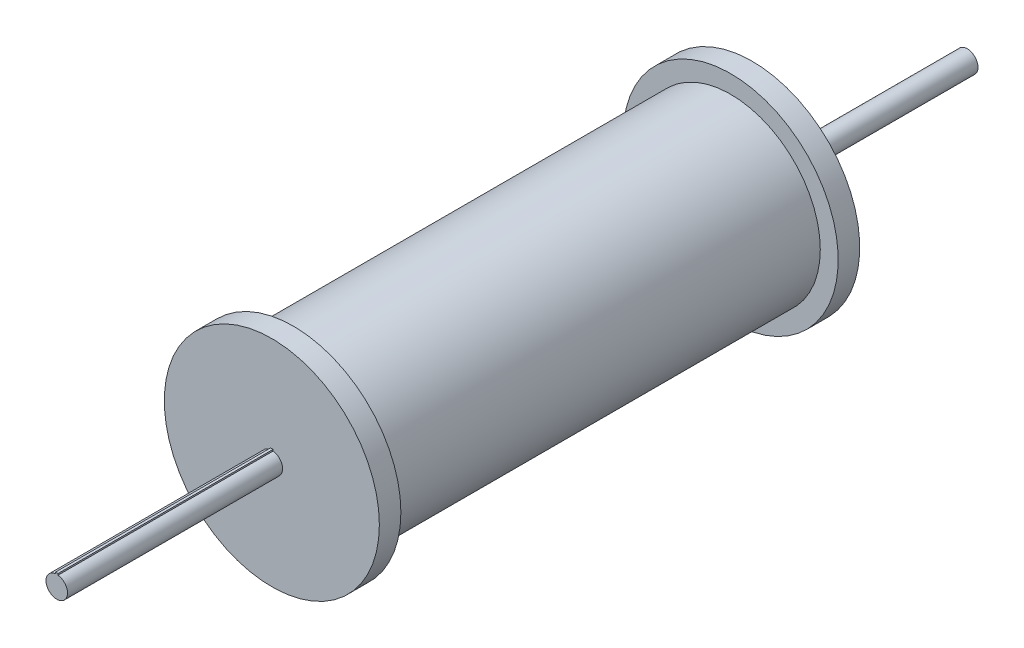
SolidWorks part; units mm, degrees
material "PVC Rígido"
ref_plane "Alzado" through (0, 0, 0) normal (0, 0, 1) x (1, 0, 0)
ref_plane "Planta" through (0, 0, 0) normal (0, 1, 0) x (1, 0, 0)
ref_plane "Vista lateral" through (0, 0, 0) normal (1, 0, 0) x (0, 0, -1)
sketch "Croquis1" plane through (0, 0, 0) normal (0, 0, 1) x (1, 0, 0)
  circle A0 centre (0, 0) radius 15
  circle A1 centre (0, 0) radius 1.5
  dimension "D1" = 30
  dimension "D2" = 3
extrude "Saliente-Extruir1" add sketch "Croquis1" along normal blind 3 contours A0
sketch "Croquis2" plane through (0, 0, 3) normal (0, 0, 1) x (1, 0, 0)
  line L2 (-0.175, 1.4898) -> (-0.175, 1.698)
  line L3 (-0.175, 1.698) -> (0.175, 1.698)
  line L4 (0.175, 1.698) -> (0.175, 1.4898)
  arc A0 (-0.175, 1.4898) -> (0.175, 1.4898) centre (0, 0) ccw
  dimension "D1" = 3
  dimension "D2" = 0.2082
  dimension "D3" = 0.35
extrude "Saliente-Extruir2" add sketch "Croquis2" along normal blind 30
sketch "Croquis3" plane through (0, 0, 0) normal (0, 0, -1) x (-1, 0, 0)
  circle A0 centre (0, 0) radius 12.5
  dimension "D1" = 25
extrude "Saliente-Extruir3" add sketch "Croquis3" along normal blind 61
sketch "Croquis4" plane through (0, 0, -61) normal (0, 0, -1) x (-1, 0, 0)
  circle A0 centre (0, 0) radius 15
  dimension "D1" = 30
extrude "Saliente-Extruir4" add sketch "Croquis4" along normal blind 3
sketch "Croquis5" plane through (0, 0, -64) normal (0, 0, -1) x (-1, 0, 0)
  circle A0 centre (0, 0) radius 1.5
  dimension "D1" = 3
extrude "Saliente-Extruir5" add sketch "Croquis5" along normal blind 30
